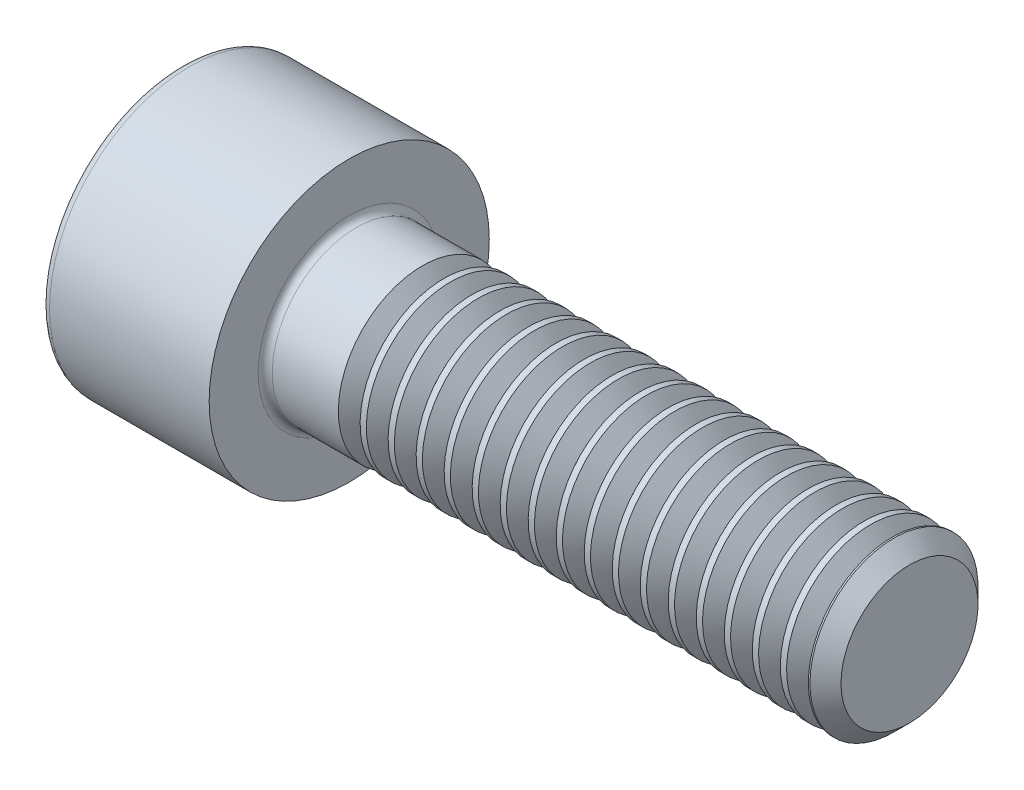
SolidWorks part; units mm, degrees
revolve "Base-Revolve" add sketch "BodySke"
sketch "BodySke" plane through (0, 0, 0) normal (0, 0, 1) x (1, 0, 0)
  line L0 (0, 0) -> (0, 5)
  line L1 (0, 5) -> (6, 5)
  line L2 (6, 5) -> (6, 3)
  line L3 (6, 3) -> (25.4455, 3)
  line L4 (26, 2.4455) -> (26, 0)
  line L5 (26, 0) -> (0, 0)
  line L6 (-31.75, 0) -> (127, 0) construction
  line L8 (26, 2.4455) -> (25.4455, 3)
  line L10 (26, -2.4455) -> (25.4455, -3) construction
  line L11 (7, 9.525) -> (7, 3.175) construction
  line L12 (6, 9.525) -> (6, 3.175) construction
  line L13 (-34, 9.525) -> (-34, 3.175) construction
  dimension "Head_ht" = 6
  dimension "Length" = 20
  dimension "Body_ch_ang" = 45
  dimension "Diameter" = 6
  dimension "Minor_dia" = 4.891
  dimension "Advance" = 1
  dimension "Thread_nom" = 20
  dimension "Thread_length" = 60
  dimension "Head_dia" = 10
cosmetic thread "ThreadCosmetic" [suppressed]
fillet "Fillet1" radius 0.25 1 edges at (6, 0, 3)
fillet "Fillet2" radius 0.3 1 edges at (0, 0, 5)
ref_plane "Plane1" through (0, 0, 0) normal (0, 0, 1) x (1, 0, 0)
ref_plane "Plane2" through (0, 0, 0) normal (0, 1, 0) x (1, 0, 0)
ref_plane "Plane3" through (0, 0, 0) normal (1, 0, 0) x (0, 0, -1)
sketch "Sketch2" plane through (0, 0, 0) normal (0, 0, 1) x (1, 0, 0)
  line L0 (0, 2.542) -> (3, 2.542)
  line L1 (3, 2.542) -> (4.4676, 0)
  line L2 (-31.75, 0) -> (127, 0) construction
  line L3 (4.4676, 0) -> (0, 0)
  line L4 (0, 0) -> (0, 2.542)
  line L6 (0, 0) -> (47.625, 0) construction
  dimension "D1" = 2.542
  dimension "D2" = 60
  dimension "Depth" = 3
revolve "Hex-PreBroach" cut sketch "Sketch2" angle 360 about L6
sketch "Sketch3" plane through (0, 0, 0) normal (-1, 0, 0) x (0, 0.5, 0.866)
  line L0 (1.4676, 2.542) -> (-1.4676, 2.542)
  line L1 (-1.4676, 2.542) -> (-2.9352, 0)
  line L2 (1.4676, 2.542) -> (2.9352, 0)
  line L3 (1.4676, -2.542) -> (2.9352, 0)
  line L4 (1.4676, -2.542) -> (-1.4676, -2.542)
  line L5 (-1.4676, -2.542) -> (-2.9352, 0)
  dimension "D1" = 2.542
  dimension "D2" = 2.542
  dimension "Hex_size" = 5.084
extrude "Hex" cut sketch "Sketch3" against normal blind 3
sketch "ThdSchSke" plane through (0, 0, 0) normal (0, 0, 1) x (1, 0, 0)
  line L0 (9, -2.4455) -> (8.6117, -3)
  line L1 (9, -2.4455) -> (9.3883, -3)
  line L2 (9.3883, -3) -> (9.3883, -3.75)
  line L3 (-3.175, 0) -> (5.1513, 0) construction
  line L4 (0, 4.7) -> (0, -4.7) construction
  line L5 (9.3883, -3.75) -> (8.6117, -3.75)
  line L6 (8.6117, -3.75) -> (8.6117, -3)
  dimension "Thread_minor" = 4.891
  dimension "Diameter" = 6
  dimension "Start" = 9
revolve "ThreadSchematic" cut sketch "ThdSchSke" angle 360 about L3
pattern_linear "ThdSchPat" count 17 spacing 1 along (1, 0, 0) of "ThreadSchematic"
equation "\"D2@Sketch3\" = \"Hex_size@Sketch3\" / 2"
equation "\"D1@Sketch3\" = \"Hex_size@Sketch3\" / 2"
equation "\"D1@Sketch2\" = \"Hex_size@Sketch3\" / 2"
equation "\"Thread_minor@ThreadCosmetic\"  =  \"Minor_dia@BodySke\""
equation "\"Depth@Sketch2\" =  \"Key_eng@Hex\""
equation "\"Thread_length@ThreadCosmetic\" = ((sgn( (\"Length@BodySke\" - \"Advance@BodySke\" * 3.0) - \"Thread_nom@BodySke\" )-1)*( (\"Length@BodySke\" - \"Advance@BodySke\" * 3.0) - \"Thread_nom@BodySke\" ))/-2+ \"Thread_nom@BodySke\""
equation "\"Thread_minor@ThdSchSke\" = \"Minor_dia@BodySke\""
equation "\"Diameter@ThdSchSke\" = \"Diameter@BodySke\""
equation "\"Overcut@ThdSchSke\" = \"Diameter@BodySke\" * 1.25"
equation "\"Start@ThdSchSke\" = \"Head_ht@BodySke\" + \"Length@BodySke\" - \"Thread_length@ThreadCosmetic\"  '---Non-countersunk---"
equation "\"Num_threads@ThdSchPat\" = int( \"Thread_length@ThreadCosmetic\" / \"Advance@BodySke\" + 0.999 )  + 1"
equation "\"Advance@ThdSchPat\" = \"Thread_length@ThreadCosmetic\" /  (\"Num_threads@ThdSchPat\" - 1) 'relax it"
equation "\"Num_threads@ThdSchPat\" = \"Num_threads@ThdSchPat\" - sgn( \"Num_threads@ThdSchPat\" - 1) '---chamfered tips only---"
